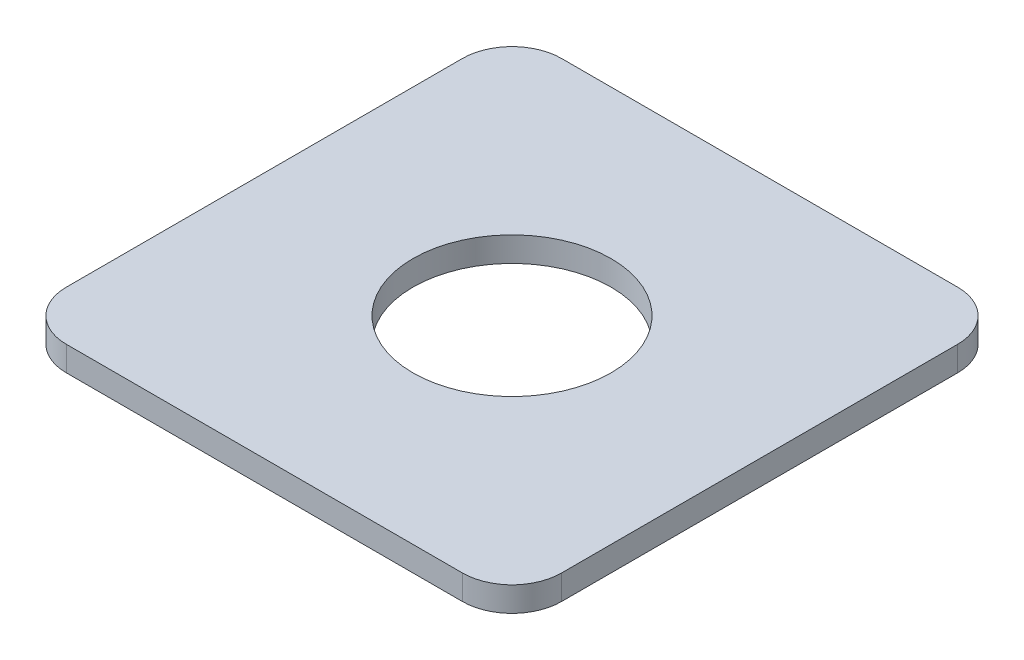
SolidWorks part; units mm, degrees
ref_plane "Front Plane" through (0, 0, 0) normal (0, 0, 1) x (1, 0, 0)
ref_plane "Top Plane" through (0, 0, 0) normal (0, 1, 0) x (1, 0, 0)
ref_plane "Right Plane" through (0, 0, 0) normal (1, 0, 0) x (0, 0, -1)
sketch "Sketch2" plane through (0, 0, 0) normal (0, 1, 0) x (1, 0, 0)
  line L1 (5, 5) -> (-5, 5)
  line L2 (5, 5) -> (5, -5)
  line L3 (5, -5) -> (-5, -5)
  line L4 (-5, 5) -> (-5, -5)
  line L5 (5, 5) -> (-5, -5) construction
  line L6 (5, -5) -> (-5, 5) construction
  point P0 (0, 0)
extrude "Boss-Extrude1" add sketch "Sketch2" along normal blind 0.5
fillet "Fillet1" radius 1 4 edges at (5, 0.25, -5) (5, 0.25, 5) (-5, 0.25, 5) (-5, 0.25, -5)
sketch "Sketch3" plane through (0, 0.5, 0) normal (0, 1, 0) x (1, 0, 0)
  circle A0 centre (0, 0) radius 2
extrude "Cut-Extrude1" cut sketch "Sketch3" against normal blind 0.5
